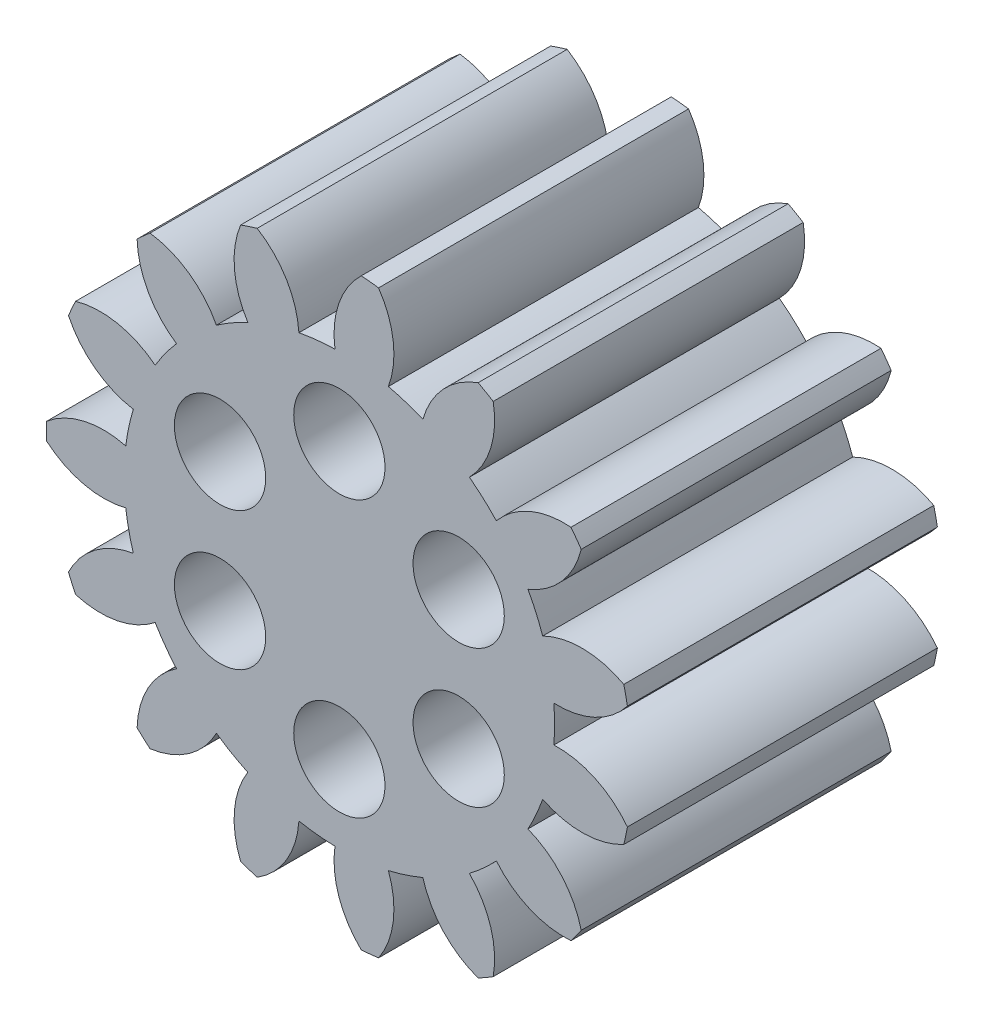
SolidWorks part; units mm, degrees
ref_plane "前视基准面" through (0, 0, 0) normal (0, 0, 1) x (1, 0, 0)
ref_plane "上视基准面" through (0, 0, 0) normal (0, 1, 0) x (1, 0, 0)
ref_plane "右视基准面" through (0, 0, 0) normal (1, 0, 0) x (0, 0, -1)
other "Configuration Table"
sketch "草图1" plane through (0, 0, 0) normal (0, 0, 1) x (1, 0, 0)
  line L0 (0, 0) -> (0, 34.0248) construction
  line L1 (0, 0) -> (12.4185, 34.1195) construction
  line L2 (0, 0) -> (3.7167, 35.3621) construction
  line L3 (0, 15) -> (4.8209, 13.2453) construction
  circle A0 centre (0, 0) radius 15 construction
  circle A1 centre (0, 0) radius 12.5
  circle A2 centre (0, 0) radius 17
  arc A3 (1.2742, 16.9522) -> (-0.2546, 12.4974) centre (4.8209, 13.2453) ccw
  arc A4 (2.2782, 16.8467) -> (2.8474, 12.1714) centre (-1.9617, 13.9582) cw
  dimension "D1" = 30
  dimension "D2" = 2.5
  dimension "D3" = 2
  dimension "D4" = 6
  dimension "D5" = 20
extrude "凸台-拉伸2" add sketch "草图1" along normal blind 5 contours A1
sketch "草图4" plane through (0, 0, 5) normal (0, 0, 1) x (1, 0, 0)
  arc A0 (2.8474, 12.1714) -> (2.2782, 16.8467) centre (-1.9617, 13.9582) ccw construction
  circle A1 centre (0, 0) radius 17
  circle A2 centre (0, 0) radius 17
  circle A3 centre (0, 0) radius 12.5
  circle A4 centre (0, 0) radius 12.5
  arc A5 (1.2742, 16.9522) -> (-0.2546, 12.4974) centre (4.8209, 13.2453) ccw construction
  arc A6 (2.8474, 12.1714) -> (2.2782, 16.8467) centre (-1.9617, 13.9582) ccw
  arc A7 (1.2742, 16.9522) -> (-0.2546, 12.4974) centre (4.8209, 13.2453) ccw
  arc A8 (8.0591, 14.9683) -> (4.8506, 11.5205) centre (9.7915, 10.1394) ccw
  arc A9 (7.5518, 9.961) -> (8.9334, 14.4635) centre (3.8852, 13.5494) ccw
  arc A10 (13.4505, 10.3963) -> (9.117, 8.5516) centre (13.069, 5.2802) ccw
  arc A11 (10.9504, 6.0282) -> (14.0439, 9.5796) centre (9.0603, 10.7977) ccw
  arc A12 (16.5162, 4.0267) -> (11.8071, 4.104) centre (14.0868, -0.4919) ccw
  arc A13 (12.4556, 1.0531) -> (16.7261, 3.0392) centre (12.6689, 6.179) ccw
  arc A14 (16.7261, -3.0392) -> (12.4556, -1.0531) centre (12.6689, -6.179) ccw
  arc A15 (11.8071, -4.104) -> (16.5162, -4.0267) centre (14.0868, 0.4919) ccw
  arc A16 (14.0439, -9.5796) -> (10.9504, -6.0282) centre (9.0603, -10.7977) ccw
  arc A17 (9.117, -8.5516) -> (13.4505, -10.3963) centre (13.069, -5.2802) ccw
  arc A18 (8.9334, -14.4635) -> (7.5518, -9.961) centre (3.8852, -13.5494) ccw
  arc A19 (4.8506, -11.5205) -> (8.0591, -14.9683) centre (9.7915, -10.1394) ccw
  arc A20 (2.2782, -16.8467) -> (2.8474, -12.1714) centre (-1.9617, -13.9582) ccw
  arc A21 (-0.2546, -12.4974) -> (1.2742, -16.9522) centre (4.8209, -13.2453) ccw
  arc A22 (-4.7709, -16.3168) -> (-2.3493, -12.2772) centre (-7.4694, -11.9536) ccw
  arc A23 (-5.3157, -11.3134) -> (-5.7311, -16.0048) centre (-0.9832, -14.0611) ccw
  arc A24 (-10.9951, -12.9657) -> (-7.1398, -10.2603) centre (-11.6856, -7.882) ccw
  arc A25 (-9.4577, -8.1732) -> (-11.7453, -12.2901) centre (-6.6174, -12.4455) ccw
  arc A26 (-15.3181, -7.3726) -> (-10.6958, -6.4692) centre (-13.8812, -2.4476) ccw
  arc A27 (-11.9644, -3.6198) -> (-15.7287, -6.4503) centre (-11.1073, -8.678) ccw
  arc A28 (-16.9925, -0.5048) -> (-12.4023, -1.5595) centre (-13.6767, 3.41) ccw
  arc A29 (-12.4023, 1.5595) -> (-16.9925, 0.5048) centre (-13.6767, -3.41) ccw
  arc A30 (-15.7287, 6.4503) -> (-11.9644, 3.6198) centre (-11.1073, 8.678) ccw
  arc A31 (-10.6958, 6.4692) -> (-15.3181, 7.3726) centre (-13.8812, 2.4476) ccw
  arc A32 (-11.7453, 12.2901) -> (-9.4577, 8.1732) centre (-6.6174, 12.4455) ccw
  arc A33 (-7.1398, 10.2603) -> (-10.9951, 12.9657) centre (-11.6856, 7.882) ccw
  arc A34 (-5.7311, 16.0048) -> (-5.3157, 11.3134) centre (-0.9832, 14.0611) ccw
  arc A35 (-2.3493, 12.2772) -> (-4.7709, 16.3168) centre (-7.4694, 11.9536) ccw
  point P13 (-9.7915, 9.961)
  point P14 (0, 0)
  point P68 (0, 0)
  point P99 (0, 0)
  circle M23 centre (0, 0) radius 12.5
  dimension "D1" = 0
  dimension "D2" = 0
  dimension "D3" = 15
extrude "凸台-拉伸4" add sketch "草图4" against normal blind 5 contours A9 A2 A8 M23 | A11 A2 A10 M23 | A13 A2 A12 M23 | A15 A2 A14 M23 | A17 A2 A16 M23 | A19 A2 A18 M23 | A21 A2 A20 M23 | A23 A2 A22 M23 | A25 A2 A24 M23 | A2 A7 A6 M23 | A35 A2 A34 M23 | A33 A2 A32 M23 | A31 A2 A30 M23 | A29 A2 A28 M23 | A27 A2 A26 M23
sketch "草图5" plane through (0, 0, 0) normal (0, 0, -1) x (-1, 0, 0)
  circle A0 centre (0, 0) radius 8 construction
  circle A1 centre (0, 8) radius 2.65
  circle A2 centre (6.9282, 4) radius 2.65
  circle A3 centre (6.9282, -4) radius 2.65
  circle A4 centre (0, -8) radius 2.65
  circle A5 centre (-6.9282, -4) radius 2.65
  circle A6 centre (-6.9282, 4) radius 2.65
  point P17 (0, 0)
  dimension "D1" = 16
  dimension "D2" = 5.3
  dimension "D3" = 6
extrude "切除-拉伸1" cut sketch "草图5" against normal blind 5
sketch "草图8" plane through (0, 0, 5) normal (0, 0, 1) x (1, 0, 0)
  circle A1 centre (6.9282, 4) radius 2.65
  circle A2 centre (6.9282, 4) radius 2.65
  circle A3 centre (0, 8) radius 2.65
  circle A4 centre (0, 8) radius 2.65
  circle A5 centre (6.9282, -4) radius 2.65
  circle A6 centre (6.9282, -4) radius 2.65
  circle A7 centre (0, -8) radius 2.65
  circle A8 centre (0, -8) radius 2.65
  circle A9 centre (-6.9282, -4) radius 2.65
  circle A10 centre (-6.9282, -4) radius 2.65
  circle A11 centre (-6.9282, 4) radius 2.65
  circle A12 centre (-6.9282, 4) radius 2.65
  arc A52 (-0.2546, 12.4974) -> (-2.3493, 12.2772) centre (0, 0) ccw
  arc A53 (-9.4577, -8.1732) -> (-11.7453, -12.2901) centre (-6.6174, -12.4455) ccw
  arc A54 (-11.7453, -12.2901) -> (-10.9951, -12.9657) centre (0, 0) ccw
  arc A55 (-10.9951, -12.9657) -> (-7.1398, -10.2603) centre (-11.6856, -7.882) ccw
  arc A56 (-7.1398, -10.2603) -> (-5.3157, -11.3134) centre (0, 0) ccw
  arc A57 (-5.3157, -11.3134) -> (-5.7311, -16.0048) centre (-0.9832, -14.0611) ccw
  arc A58 (-5.7311, -16.0048) -> (-4.7709, -16.3168) centre (0, 0) ccw
  arc A59 (-4.7709, -16.3168) -> (-2.3493, -12.2772) centre (-7.4694, -11.9536) ccw
  arc A60 (-2.3493, -12.2772) -> (-0.2546, -12.4974) centre (0, 0) ccw
  arc A61 (-0.2546, -12.4974) -> (1.2742, -16.9522) centre (4.8209, -13.2453) ccw
  arc A62 (1.2742, -16.9522) -> (2.2782, -16.8467) centre (0, 0) ccw
  arc A63 (2.2782, -16.8467) -> (2.8474, -12.1714) centre (-1.9617, -13.9582) ccw
  arc A64 (2.8474, -12.1714) -> (4.8506, -11.5205) centre (0, 0) ccw
  arc A65 (4.8506, -11.5205) -> (8.0591, -14.9683) centre (9.7915, -10.1394) ccw
  arc A66 (8.0591, -14.9683) -> (8.9334, -14.4635) centre (0, 0) ccw
  arc A67 (8.9334, -14.4635) -> (7.5518, -9.961) centre (3.8852, -13.5494) ccw
  arc A68 (7.5518, -9.961) -> (9.117, -8.5516) centre (0, 0) ccw
  arc A69 (9.117, -8.5516) -> (13.4505, -10.3963) centre (13.069, -5.2802) ccw
  arc A70 (13.4505, -10.3963) -> (14.0439, -9.5796) centre (0, 0) ccw
  arc A71 (14.0439, -9.5796) -> (10.9504, -6.0282) centre (9.0603, -10.7977) ccw
  arc A72 (10.9504, -6.0282) -> (11.8071, -4.104) centre (0, 0) ccw
  arc A73 (11.8071, -4.104) -> (16.5162, -4.0267) centre (14.0868, 0.4919) ccw
  arc A74 (16.5162, -4.0267) -> (16.7261, -3.0392) centre (0, 0) ccw
  arc A75 (16.7261, -3.0392) -> (12.4556, -1.0531) centre (12.6689, -6.179) ccw
  arc A76 (12.4556, -1.0531) -> (12.4556, 1.0531) centre (0, 0) ccw
  arc A77 (12.4556, 1.0531) -> (16.7261, 3.0392) centre (12.6689, 6.179) ccw
  arc A78 (16.7261, 3.0392) -> (16.5162, 4.0267) centre (0, 0) ccw
  arc A79 (16.5162, 4.0267) -> (11.8071, 4.104) centre (14.0868, -0.4919) ccw
  arc A80 (11.8071, 4.104) -> (10.9504, 6.0282) centre (0, 0) ccw
  arc A81 (10.9504, 6.0282) -> (14.0439, 9.5796) centre (9.0603, 10.7977) ccw
  arc A82 (14.0439, 9.5796) -> (13.4505, 10.3963) centre (0, 0) ccw
  arc A83 (13.4505, 10.3963) -> (9.117, 8.5516) centre (13.069, 5.2802) ccw
  arc A84 (9.117, 8.5516) -> (7.5518, 9.961) centre (0, 0) ccw
  arc A85 (7.5518, 9.961) -> (8.9334, 14.4635) centre (3.8852, 13.5494) ccw
  arc A86 (8.9334, 14.4635) -> (8.0591, 14.9683) centre (0, 0) ccw
  arc A87 (8.0591, 14.9683) -> (4.8506, 11.5205) centre (9.7915, 10.1394) ccw
  arc A88 (4.8506, 11.5205) -> (2.8474, 12.1714) centre (0, 0) ccw
  arc A89 (2.8474, 12.1714) -> (2.2782, 16.8467) centre (-1.9617, 13.9582) ccw
  arc A90 (2.2782, 16.8467) -> (1.2742, 16.9522) centre (0, 0) ccw
  arc A91 (1.2742, 16.9522) -> (-0.2546, 12.4974) centre (4.8209, 13.2453) ccw
  arc A92 (-0.2546, 12.4974) -> (-2.3493, 12.2772) centre (0, 0) ccw
  arc A93 (-9.4577, -8.1732) -> (-11.7453, -12.2901) centre (-6.6174, -12.4455) ccw
  arc A94 (-11.7453, -12.2901) -> (-10.9951, -12.9657) centre (0, 0) ccw
  arc A95 (-10.9951, -12.9657) -> (-7.1398, -10.2603) centre (-11.6856, -7.882) ccw
  arc A96 (-7.1398, -10.2603) -> (-5.3157, -11.3134) centre (0, 0) ccw
  arc A97 (-5.3157, -11.3134) -> (-5.7311, -16.0048) centre (-0.9832, -14.0611) ccw
  arc A98 (-5.7311, -16.0048) -> (-4.7709, -16.3168) centre (0, 0) ccw
  arc A99 (-4.7709, -16.3168) -> (-2.3493, -12.2772) centre (-7.4694, -11.9536) ccw
  arc A100 (-2.3493, -12.2772) -> (-0.2546, -12.4974) centre (0, 0) ccw
  arc A101 (-0.2546, -12.4974) -> (1.2742, -16.9522) centre (4.8209, -13.2453) ccw
  arc A102 (1.2742, -16.9522) -> (2.2782, -16.8467) centre (0, 0) ccw
  arc A103 (2.2782, -16.8467) -> (2.8474, -12.1714) centre (-1.9617, -13.9582) ccw
  arc A104 (2.8474, -12.1714) -> (4.8506, -11.5205) centre (0, 0) ccw
  arc A105 (4.8506, -11.5205) -> (8.0591, -14.9683) centre (9.7915, -10.1394) ccw
  arc A106 (8.0591, -14.9683) -> (8.9334, -14.4635) centre (0, 0) ccw
  arc A107 (8.9334, -14.4635) -> (7.5518, -9.961) centre (3.8852, -13.5494) ccw
  arc A108 (7.5518, -9.961) -> (9.117, -8.5516) centre (0, 0) ccw
  arc A109 (9.117, -8.5516) -> (13.4505, -10.3963) centre (13.069, -5.2802) ccw
  arc A110 (13.4505, -10.3963) -> (14.0439, -9.5796) centre (0, 0) ccw
  arc A111 (14.0439, -9.5796) -> (10.9504, -6.0282) centre (9.0603, -10.7977) ccw
  arc A112 (10.9504, -6.0282) -> (11.8071, -4.104) centre (0, 0) ccw
  arc A113 (11.8071, -4.104) -> (16.5162, -4.0267) centre (14.0868, 0.4919) ccw
  arc A114 (16.5162, -4.0267) -> (16.7261, -3.0392) centre (0, 0) ccw
  arc A115 (16.7261, -3.0392) -> (12.4556, -1.0531) centre (12.6689, -6.179) ccw
  arc A116 (12.4556, -1.0531) -> (12.4556, 1.0531) centre (0, 0) ccw
  arc A117 (12.4556, 1.0531) -> (16.7261, 3.0392) centre (12.6689, 6.179) ccw
  arc A118 (16.7261, 3.0392) -> (16.5162, 4.0267) centre (0, 0) ccw
  arc A119 (16.5162, 4.0267) -> (11.8071, 4.104) centre (14.0868, -0.4919) ccw
  arc A120 (11.8071, 4.104) -> (10.9504, 6.0282) centre (0, 0) ccw
  arc A121 (10.9504, 6.0282) -> (14.0439, 9.5796) centre (9.0603, 10.7977) ccw
  arc A122 (14.0439, 9.5796) -> (13.4505, 10.3963) centre (0, 0) ccw
  arc A123 (13.4505, 10.3963) -> (9.117, 8.5516) centre (13.069, 5.2802) ccw
  arc A124 (9.117, 8.5516) -> (7.5518, 9.961) centre (0, 0) ccw
  arc A125 (7.5518, 9.961) -> (8.9334, 14.4635) centre (3.8852, 13.5494) ccw
  arc A126 (8.9334, 14.4635) -> (8.0591, 14.9683) centre (0, 0) ccw
  arc A127 (8.0591, 14.9683) -> (4.8506, 11.5205) centre (9.7915, 10.1394) ccw
  arc A128 (4.8506, 11.5205) -> (2.8474, 12.1714) centre (0, 0) ccw
  arc A129 (2.8474, 12.1714) -> (2.2782, 16.8467) centre (-1.9617, 13.9582) ccw
  arc A130 (2.2782, 16.8467) -> (1.2742, 16.9522) centre (0, 0) ccw
  arc A131 (1.2742, 16.9522) -> (-0.2546, 12.4974) centre (4.8209, 13.2453) ccw
  arc A152 (-2.3493, 12.2772) -> (-4.7709, 16.3168) centre (-7.4694, 11.9536) ccw
  arc A153 (-2.3493, 12.2772) -> (-4.7709, 16.3168) centre (-7.4694, 11.9536) ccw
  arc A154 (-4.7709, 16.3168) -> (-5.7311, 16.0048) centre (0, 0) ccw
  arc A155 (-4.7709, 16.3168) -> (-5.7311, 16.0048) centre (0, 0) ccw
  arc A156 (-5.7311, 16.0048) -> (-5.3157, 11.3134) centre (-0.9832, 14.0611) ccw
  arc A157 (-5.7311, 16.0048) -> (-5.3157, 11.3134) centre (-0.9832, 14.0611) ccw
  arc A158 (-5.3157, 11.3134) -> (-7.1398, 10.2603) centre (0, 0) ccw
  arc A159 (-5.3157, 11.3134) -> (-7.1398, 10.2603) centre (0, 0) ccw
  arc A160 (-7.1398, 10.2603) -> (-10.9951, 12.9657) centre (-11.6856, 7.882) ccw
  arc A161 (-7.1398, 10.2603) -> (-10.9951, 12.9657) centre (-11.6856, 7.882) ccw
  arc A162 (-10.9951, 12.9657) -> (-11.7453, 12.2901) centre (0, 0) ccw
  arc A163 (-10.9951, 12.9657) -> (-11.7453, 12.2901) centre (0, 0) ccw
  arc A164 (-11.7453, 12.2901) -> (-9.4577, 8.1732) centre (-6.6174, 12.4455) ccw
  arc A165 (-11.7453, 12.2901) -> (-9.4577, 8.1732) centre (-6.6174, 12.4455) ccw
  arc A166 (-9.4577, 8.1732) -> (-10.6958, 6.4692) centre (0, 0) ccw
  arc A167 (-9.4577, 8.1732) -> (-10.6958, 6.4692) centre (0, 0) ccw
  arc A168 (-10.6958, 6.4692) -> (-15.3181, 7.3726) centre (-13.8812, 2.4476) ccw
  arc A169 (-10.6958, 6.4692) -> (-15.3181, 7.3726) centre (-13.8812, 2.4476) ccw
  arc A170 (-15.3181, 7.3726) -> (-15.7287, 6.4503) centre (0, 0) ccw
  arc A171 (-15.3181, 7.3726) -> (-15.7287, 6.4503) centre (0, 0) ccw
  arc A172 (-15.7287, 6.4503) -> (-11.9644, 3.6198) centre (-11.1073, 8.678) ccw
  arc A173 (-15.7287, 6.4503) -> (-11.9644, 3.6198) centre (-11.1073, 8.678) ccw
  arc A174 (-11.9644, 3.6198) -> (-12.4023, 1.5595) centre (0, 0) ccw
  arc A175 (-11.9644, 3.6198) -> (-12.4023, 1.5595) centre (0, 0) ccw
  arc A176 (-12.4023, 1.5595) -> (-16.9925, 0.5048) centre (-13.6767, -3.41) ccw
  arc A177 (-12.4023, 1.5595) -> (-16.9925, 0.5048) centre (-13.6767, -3.41) ccw
  arc A178 (-16.9925, 0.5048) -> (-16.9925, -0.5048) centre (0, 0) ccw
  arc A179 (-16.9925, 0.5048) -> (-16.9925, -0.5048) centre (0, 0) ccw
  arc A180 (-16.9925, -0.5048) -> (-12.4023, -1.5595) centre (-13.6767, 3.41) ccw
  arc A181 (-16.9925, -0.5048) -> (-12.4023, -1.5595) centre (-13.6767, 3.41) ccw
  arc A182 (-12.4023, -1.5595) -> (-11.9644, -3.6198) centre (0, 0) ccw
  arc A183 (-12.4023, -1.5595) -> (-11.9644, -3.6198) centre (0, 0) ccw
  arc A184 (-11.9644, -3.6198) -> (-15.7287, -6.4503) centre (-11.1073, -8.678) ccw
  arc A185 (-11.9644, -3.6198) -> (-15.7287, -6.4503) centre (-11.1073, -8.678) ccw
  arc A186 (-15.7287, -6.4503) -> (-15.3181, -7.3726) centre (0, 0) ccw
  arc A187 (-15.7287, -6.4503) -> (-15.3181, -7.3726) centre (0, 0) ccw
  arc A188 (-15.3181, -7.3726) -> (-10.6958, -6.4692) centre (-13.8812, -2.4476) ccw
  arc A189 (-15.3181, -7.3726) -> (-10.6958, -6.4692) centre (-13.8812, -2.4476) ccw
  arc A190 (-10.6958, -6.4692) -> (-9.4577, -8.1732) centre (0, 0) ccw
  arc A191 (-10.6958, -6.4692) -> (-9.4577, -8.1732) centre (0, 0) ccw
  dimension "D1" = 0
  dimension "D2" = 0
  dimension "D3" = 0
  dimension "D4" = 0
  dimension "D5" = 0
  dimension "D6" = 0
  dimension "D7" = 0
extrude "凸台-拉伸6" add sketch "草图8" along normal blind 13
